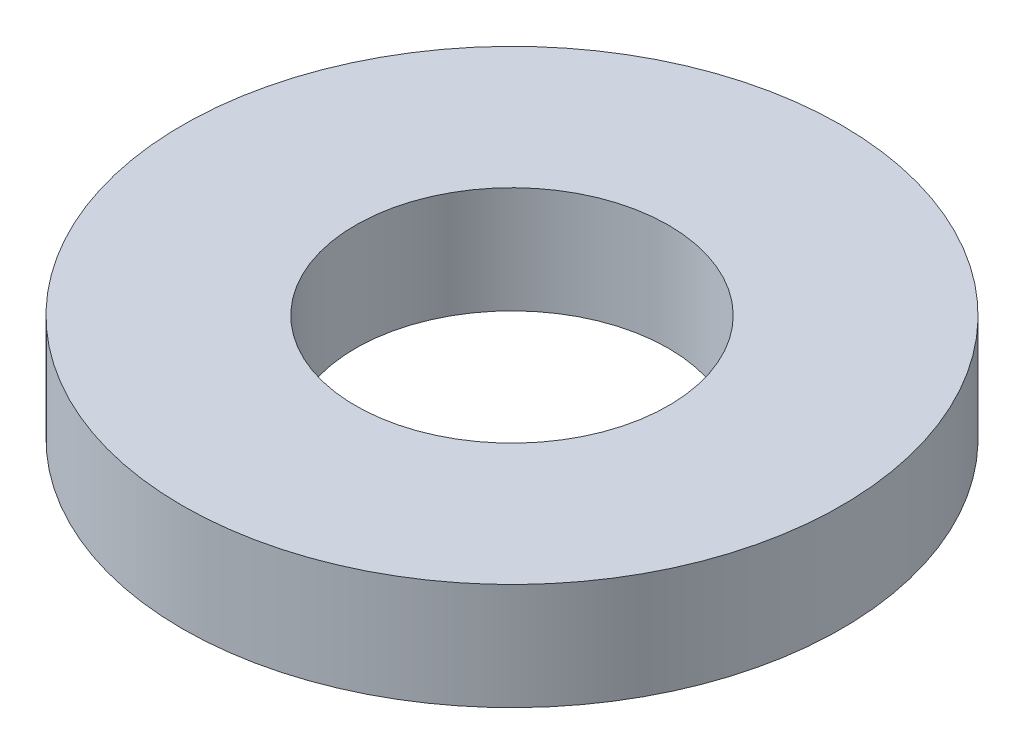
SolidWorks part; units mm, degrees
ref_plane "Front Plane" through (0, 0, 0) normal (0, 0, 1) x (1, 0, 0)
ref_plane "Top Plane" through (0, 0, 0) normal (0, 1, 0) x (1, 0, 0)
ref_plane "Right Plane" through (0, 0, 0) normal (1, 0, 0) x (0, 0, -1)
sketch "Sketch1" plane through (0, 0, 0) normal (0, 1, 0) x (1, 0, 0)
  circle A0 centre (0, 0) radius 12.36
  dimension "D1" = 24.72
extrude "Boss-Extrude1" add sketch "Sketch1" along normal blind 4
sketch "Sketch2" plane through (0, 0, 0) normal (0, -1, 0) x (-1, 0, 0)
  circle A0 centre (0, 0) radius 5.8674
  dimension "D1" = 11.7348
extrude "Cut-Extrude1" cut sketch "Sketch2" against normal through all
sketch "Sketch4" plane through (0, 4, 0) normal (0, 1, 0) x (1, 0, 0)
  circle A0 centre (0, 0) radius 12.0429 construction
  text T0 "<b>1mm</b>" font "Cambria" height 5.08
extrude "Cut-Extrude2" [suppressed] cut sketch "Sketch4" against normal blind 0.2
